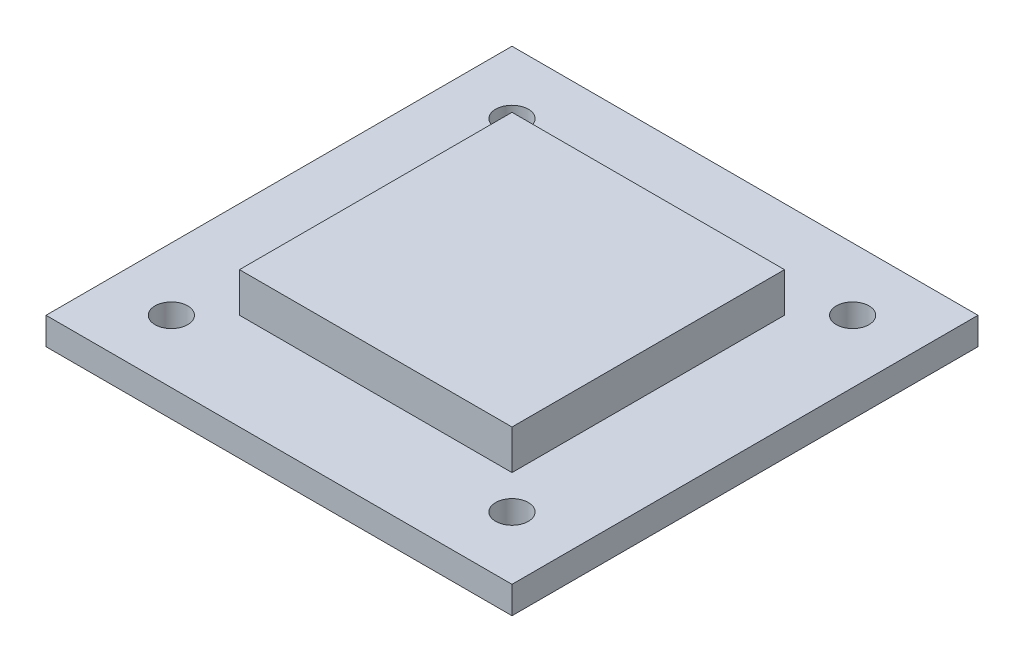
SolidWorks part; units mm, degrees
ref_plane "Front Plane" through (0, 0, 0) normal (0, 0, 1) x (1, 0, 0)
ref_plane "Top Plane" through (0, 0, 0) normal (0, 1, 0) x (1, 0, 0)
ref_plane "Right Plane" through (0, 0, 0) normal (1, 0, 0) x (0, 0, -1)
sketch "Sketch1" plane through (0, 0, 0) normal (0, 1, 0) x (1, 0, 0)
  line L1 (-17.1, 17.1) -> (17.1, 17.1)
  line L2 (-17.1, 17.1) -> (-17.1, -17.1)
  line L3 (-17.1, -17.1) -> (17.1, -17.1)
  line L4 (17.1, 17.1) -> (17.1, -17.1)
  line L5 (-17.1, 17.1) -> (17.1, -17.1) construction
  line L6 (-17.1, -17.1) -> (17.1, 17.1) construction
  point P0 (0, 0)
  dimension "D1" = 34.2
extrude "Boss-Extrude1" add sketch "Sketch1" along normal mid plane 7.8
sketch "Sketch5" plane through (0, 3.9, 0) normal (0, 1, 0) x (1, 0, 0)
  line L1 (12.5, -12.5) -> (-12.5, -12.5) construction
  line L2 (12.5, -12.5) -> (12.5, 12.5) construction
  line L3 (12.5, 12.5) -> (-12.5, 12.5) construction
  line L4 (-12.5, -12.5) -> (-12.5, 12.5) construction
  line L7 (-12.5, -12.5) -> (0, 0) construction
  line L8 (0, 0) -> (-12.5, 12.5) construction
  point P1 (-12.5, 12.5)
  point P2 (12.5, -12.5)
  point P3 (12.5, 12.5)
  point P4 (-12.5, -12.5)
  dimension "D1" = 25
hole_wizard "M2 Clearance Hole1" positions "Sketch5" profile "Sketch8" hole size "M2" standard "ISO" end condition through all
sketch "Sketch8" plane through (-12.5, 3.9, -12.5) normal (1, 0, 0) x (0, 0, 1)
  line L0 (0, 0) -> (0, 7.8)
  line L1 (0, 7.8) -> (1.2, 7.8)
  line L2 (1.2, 7.8) -> (1.2, 0)
  line L5 (1.2, 0) -> (0, 0)
  line L11 (0, -6.35) -> (0, 107.95) construction
  dimension "Thru Hole Dia." = 2.4
  dimension "Thru Hole Depth" = 7.8
sketch "Sketch9" plane through (0, 3.9, 0) normal (0, 1, 0) x (1, 0, 0)
  line L1 (10, -10) -> (-10, -10)
  line L2 (10, -10) -> (10, 10)
  line L3 (10, 10) -> (-10, 10)
  line L4 (-10, -10) -> (-10, 10)
  line L5 (10, -10) -> (-10, 10) construction
  line L6 (10, 10) -> (-10, -10) construction
  line L14 (17.1, -17.1) -> (17.1, 17.1)
  line L15 (17.1, 17.1) -> (-17.1, 17.1)
  line L16 (-17.1, 17.1) -> (-17.1, -17.1)
  line L17 (-17.1, -17.1) -> (17.1, -17.1)
  line L18 (17.1, -17.1) -> (17.1, 17.1)
  line L19 (17.1, 17.1) -> (-17.1, 17.1)
  line L20 (-17.1, 17.1) -> (-17.1, -17.1)
  line L21 (-17.1, -17.1) -> (17.1, -17.1)
  point P0 (0, 0)
  circle M9 centre (-12.5, 12.5) radius 1.2
  circle M10 centre (12.5, -12.5) radius 1.2
  circle M11 centre (12.5, 12.5) radius 1.2
  circle M12 centre (-12.5, -12.5) radius 1.2
  line M13 (17.1, -17.1) -> (17.1, 17.1)
  line M14 (17.1, 17.1) -> (-17.1, 17.1)
  line M15 (-17.1, 17.1) -> (-17.1, -17.1)
  line M16 (-17.1, -17.1) -> (17.1, -17.1)
  dimension "D1" = 20
  dimension "D2" = 0
extrude "Cut-Extrude1" cut sketch "Sketch9" against normal offset from surface (2.9 mm away) 1 contours L1 L4 L3 L2 M16 M13 M14 M15 M10 M12 M11 M9 up to plane "Top Plane"
mirror "Mirror1" about plane through (0, 0, 0) normal (0, 1, 0) of "Cut-Extrude1"
